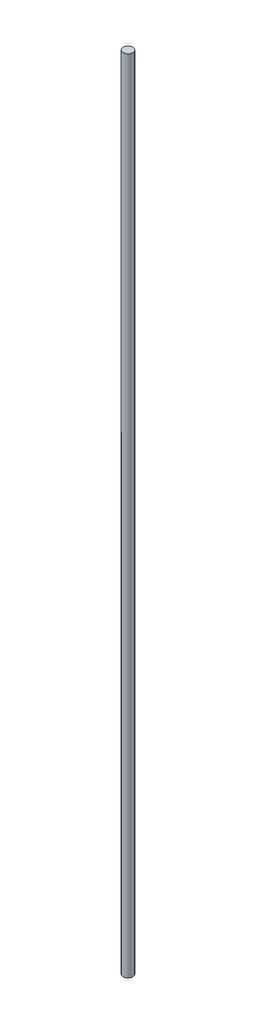
SolidWorks part; units mm, degrees
ref_plane "正面" through (0, 0, 0) normal (0, 0, 1) x (1, 0, 0)
ref_plane "平面" through (0, 0, 0) normal (0, 1, 0) x (1, 0, 0)
ref_plane "右側面" through (0, 0, 0) normal (1, 0, 0) x (0, 0, -1)
sketch "ｽｹｯﾁ1" plane through (0, 0, 0) normal (0, 1, 0) x (1, 0, 0)
  circle A0 centre (0, 0) radius 0.6
  dimension "D1" = 1.2
extrude "ﾎﾞｽ - 押し出し1" add sketch "ｽｹｯﾁ1" along normal blind 100
